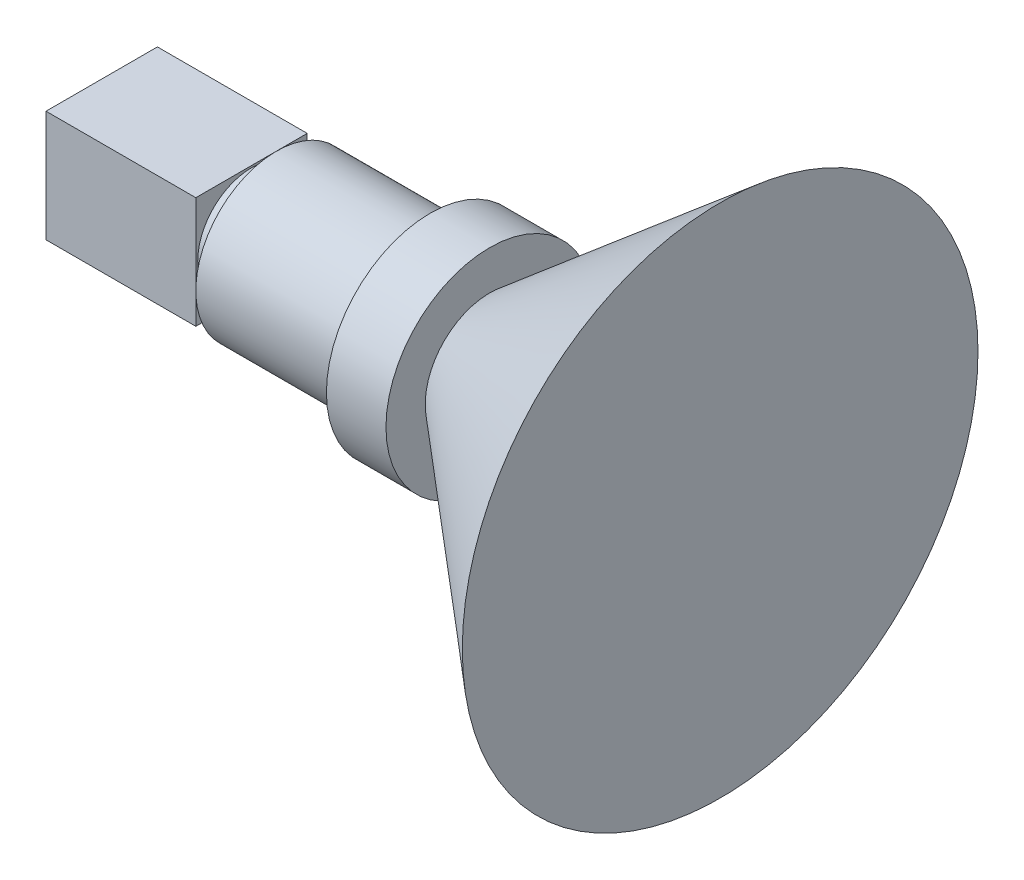
SolidWorks part; units mm, degrees
ref_plane "Front Plane" through (0, 0, 0) normal (0, 0, 1) x (1, 0, 0)
ref_plane "Top Plane" through (0, 0, 0) normal (0, 1, 0) x (1, 0, 0)
ref_plane "Right Plane" through (0, 0, 0) normal (1, 0, 0) x (0, 0, -1)
sketch "Sketch2" plane through (0, 0, 0) normal (0, 1, 0) x (1, 0, 0)
  line L1 (-19.5, -14.5) -> (19.5, -14.5)
  line L2 (-19.5, -14.5) -> (-19.5, 14.5)
  line L3 (-19.5, 14.5) -> (19.5, 14.5)
  line L4 (19.5, -14.5) -> (19.5, 14.5)
  line L5 (-19.5, -14.5) -> (19.5, 14.5) construction
  line L6 (-19.5, 14.5) -> (19.5, -14.5) construction
  point P0 (0, 0)
  dimension "D1" = 39
  dimension "D2" = 29
extrude "Boss-Extrude1" add sketch "Sketch2" along normal mid plane 29
sketch "Sketch4" plane through (19.5, 0, 0) normal (1, 0, 0) x (0, 0, -1)
  circle A0 centre (0, 0) radius 14
  dimension "D1" = 28
extrude "Boss-Extrude2" add sketch "Sketch4" along normal blind 6.5
sketch "Sketch5" plane through (26, 0, 0) normal (1, 0, 0) x (0, 0, -1)
  circle A0 centre (0, 0) radius 21
  dimension "D1" = 42
extrude "Boss-Extrude3" add sketch "Sketch5" along normal blind 40
sketch "Sketch6" plane through (66, 0, 0) normal (1, 0, 0) x (0, 0, -1)
  circle A0 centre (0, 0) radius 27
  dimension "D1" = 54
extrude "Boss-Extrude4" add sketch "Sketch6" along normal blind 15.5
sketch "Sketch7" plane through (0, -14.5, 0) normal (0, -1, 0) x (1, 0, 0)
  line L1 (-16.5, -11.5) -> (16.5, -11.5) construction
  line L2 (-16.5, -11.5) -> (-16.5, 11.5) construction
  line L3 (-16.5, 11.5) -> (16.5, 11.5) construction
  line L4 (16.5, -11.5) -> (16.5, 11.5) construction
  line L5 (-16.5, -11.5) -> (16.5, 11.5) construction
  line L6 (-16.5, 11.5) -> (16.5, -11.5) construction
  point P0 (0, 0)
  dimension "D1" = 33
  dimension "D2" = 23
hole_wizard "M3x0.5 Tapped Hole1" positions "Sketch8" profile "Sketch10" tap size "M3x0.5" standard "ANSI Metric"
sketch "Sketch8" plane through (0, -14.5, 0) normal (0, -1, 0) x (-1, 0, 0)
  point P0 (-16.5, 11.5)
  point P3 (16.5, 11.5)
  point P6 (16.5, -11.5)
  point P9 (-16.5, -11.5)
sketch "Sketch10" plane through (16.5, -14.5, -11.5) normal (1, 0, 0) x (0, 0, -1)
  line L0 (0, 0) -> (0, 5.7511)
  line L1 (0, 5.7511) -> (1.25, 5)
  line L2 (1.25, 5) -> (1.25, 0)
  line L5 (1.25, 0) -> (0, 0)
  line L10 (0, 5.7511) -> (-1.25, 5) construction
  line L11 (0, -6.35) -> (0, 107.95) construction
  dimension "Tap Drill Dia." = 2.5
  dimension "Tap Drill Depth" = 5
  dimension "Drill Angle" = 118
cosmetic thread "Hole Thread1" parameters "D1"=6, "D2"=3
cosmetic thread "Hole Thread2" parameters "D1"=6, "D2"=3
cosmetic thread "Hole Thread3" parameters "D1"=6, "D2"=3
cosmetic thread "Hole Thread4" parameters "D1"=6, "D2"=3
sketch "Sketch12" plane through (0, 0, 0) normal (0, 0, 1) x (1, 0, 0)
  line L0 (61.5, 0) -> (141.5, 67.128)
  line L2 (141.5, 67.128) -> (141.5, -67.128) construction
  line L3 (141.5, -67.128) -> (61.5, 0) construction
  line L4 (61.5, 0) -> (141.5, 0) construction
  line L5 (81.5, -27) -> (81.5, 27) construction
  line L6 (61.5, 0) -> (141.5, 0)
  line L7 (141.5, 0) -> (141.5, 67.128)
  dimension "D1" = 80
  dimension "D2" = 20
  dimension "D3" = 80
revolve "Revolve1" add sketch "Sketch12" angle 360 about L6
